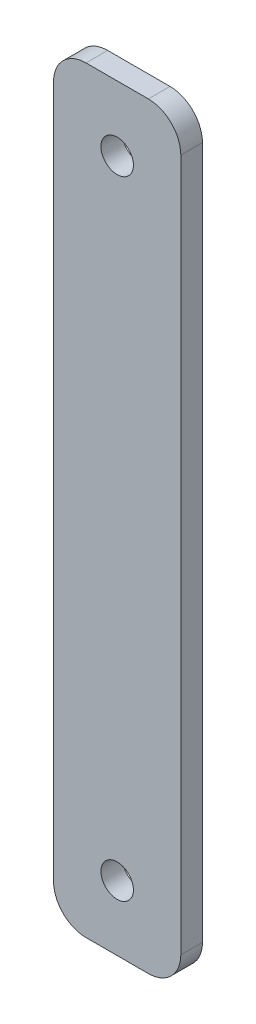
SolidWorks part; units mm, degrees
ref_plane "Front Plane" through (0, 0, 0) normal (0, 0, 1) x (1, 0, 0)
ref_plane "Top Plane" through (0, 0, 0) normal (0, 1, 0) x (1, 0, 0)
ref_plane "Right Plane" through (0, 0, 0) normal (1, 0, 0) x (0, 0, -1)
sketch "Sketch1" plane through (0, 0, 0) normal (0, 0, 1) x (1, 0, 0)
  line L0 (0, 0) -> (0, -29) construction
  line L1 (2.88, -35) -> (-2.88, -35)
  line L2 (5.88, -32) -> (5.88, 32)
  line L3 (2.88, 35) -> (-2.88, 35)
  line L4 (-5.88, -32) -> (-5.88, 32)
  line L5 (5.88, -35) -> (-5.88, 35) construction
  line L6 (5.88, 35) -> (-5.88, -35) construction
  line L7 (0, 0) -> (0, 29) construction
  arc A0 (-2.88, 35) -> (-5.88, 32) centre (-2.88, 32) ccw
  arc A1 (5.88, 32) -> (2.88, 35) centre (2.88, 32) ccw
  arc A2 (2.88, -35) -> (5.88, -32) centre (2.88, -32) ccw
  arc A3 (-2.88, -35) -> (-5.88, -32) centre (-2.88, -32) cw
  circle A4 centre (0, -29) radius 1.5
  circle A5 centre (0, 29) radius 1.5
  point P0 (0, 0)
  dimension "D3" = 3
  dimension "D4" = 3
  dimension "D5" = 3
  dimension "D6" = 3
  dimension "D8" = 29
  dimension "D1" = 70
  dimension "D2" = 11.76
  dimension "D7" = 29
extrude "Boss-Extrude1" add sketch "Sketch1" along normal blind 2
